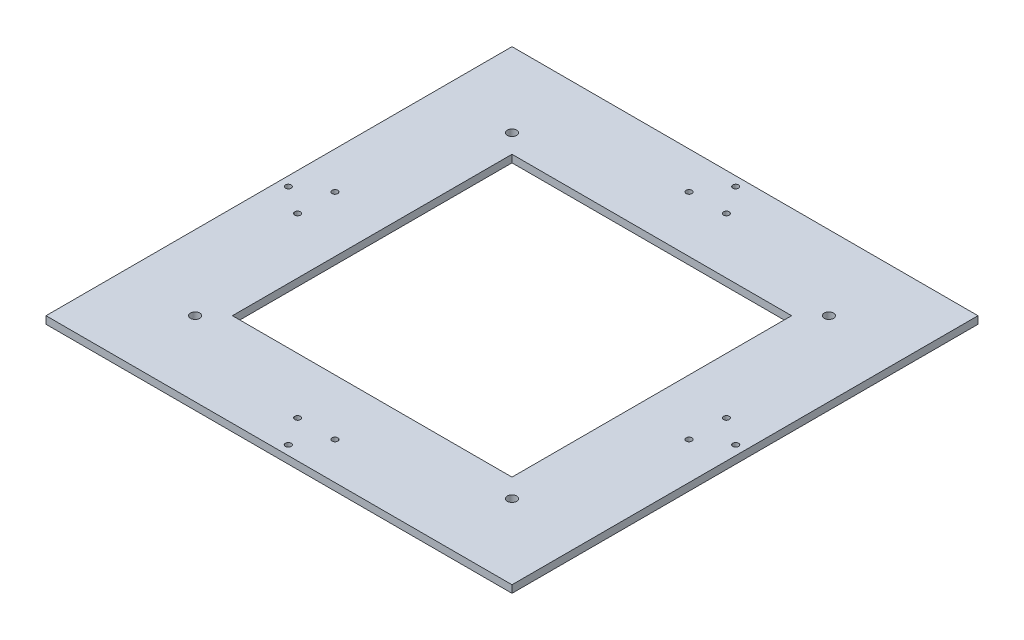
SolidWorks part; units mm, degrees
ref_plane "Alzado" through (0, 0, 0) normal (0, 0, 1) x (1, 0, 0)
ref_plane "Planta" through (0, 0, 0) normal (0, 1, 0) x (1, 0, 0)
ref_plane "Vista lateral" through (0, 0, 0) normal (1, 0, 0) x (0, 0, -1)
sketch "Croquis1" plane through (0, 0, 0) normal (0, 1, 0) x (1, 0, 0)
  line L0 (125, 40) -> (125, 0) construction
  line L1 (0, 0) -> (250, 0)
  line L2 (0, 0) -> (0, 250)
  line L3 (0, 250) -> (250, 250)
  line L4 (250, 0) -> (250, 250)
  line L5 (40, 40) -> (210, 40) construction
  line L6 (40, 40) -> (40, 210) construction
  line L7 (40, 210) -> (210, 210) construction
  line L8 (210, 40) -> (210, 210) construction
  line L9 (210, 125) -> (250, 125) construction
  circle A0 centre (40, 210) radius 2.5
  circle A1 centre (210, 210) radius 2.5
  circle A2 centre (210, 40) radius 2.5
  circle A3 centre (40, 40) radius 2.5
  dimension "D3" = 5
  dimension "D1" = 250
  dimension "D2" = 170
extrude "Saliente-Extruir1" add sketch "Croquis1" along normal blind 4
sketch "Croquis2" plane through (0, 4, 0) normal (0, 1, 0) x (1, 0, 0)
  line L0 (50, 125) -> (0, 125) construction
  line L1 (50, 50) -> (200, 50)
  line L2 (50, 50) -> (50, 150.0904)
  line L3 (50, 200) -> (200, 200)
  line L4 (200, 50) -> (200, 200)
  line L5 (0, 250) -> (0, 0) construction
  line L6 (125, 50) -> (125, 0) construction
  line L7 (0, 0) -> (250, 0) construction
  line L8 (50, 125) -> (200, 125) construction
  line L9 (125, 200) -> (125, 50) construction
  line L10 (48, 151.5) -> (48, 125) construction
  line L19 (50, 50) -> (200, 50) construction
  line L20 (50, 50) -> (50, 200) construction
  line L21 (50, 200) -> (200, 200) construction
  line L22 (200, 50) -> (200, 200) construction
  line L24 (50, 150.0904) -> (50, 172.9096)
  line L27 (59.9079, 125) -> (59.9079, 200) construction
  line L28 (50, 161.5) -> (34.9079, 161.5) construction
  line L29 (50, 150.0904) -> (125, 150.0904) construction
  line L30 (88.5, 200) -> (88.5, 125.0904) construction
  line L31 (78.5, 200) -> (98.5, 200)
  line L44 (121.5, 50) -> (101.5, 50)
  line L59 (88.5, 162.5452) -> (125, 162.5452) construction
  line L60 (42.454, 161.5) -> (42.454, 125) construction
  line L61 (25, 103.5) -> (25, 123.5) [skipped]
  line L65 (50, 150.0904) -> (50, 200)
  line L66 (125.0904, 175) -> (147.9096, 175) [skipped]
  line L69 (175, 146.5) -> (175, 126.5) [skipped]
  line L71 (150, 99.9096) -> (150, 77.0904) [skipped]
  line L72 (74.9096, 75) -> (52.0904, 75) [skipped]
  point P18 (50, 125)
  point P19 (125, 200)
  dimension "D1" = 150
  dimension "D2" = 150
  dimension "D4" = 4
  dimension "D6" = 36.5
extrude "Cortar-Extruir1" cut sketch "Croquis2" against normal blind 4
sketch "Croquis3" plane through (0, 4, 0) normal (0, 1, 0) x (1, 0, 0)
  line L0 (75, 175) -> (75, 75)
  line L1 (50, 200) -> (200, 200)
  line L2 (50, 200) -> (50, 50)
  line L3 (50, 50) -> (200, 50)
  line L4 (200, 200) -> (200, 50)
  line L5 (75, 75) -> (175, 75)
  line L6 (175, 175) -> (175, 75)
  line L7 (75, 175) -> (175, 175)
  dimension "D1" = 25
extrude "Saliente-Extruir2" add sketch "Croquis3" against normal up to surface (4 mm away) up to face at (125, 0, -125)
sketch "Croquis4" plane through (0, 4, 0) normal (0, 1, 0) x (1, 0, 0)
  line L0 (125, 0) -> (125, 75) construction
  line L1 (0, 0) -> (250, 0) construction
  line L2 (75, 75) -> (175, 75) construction
  line L3 (115, 20) -> (125, 20) construction
  line L4 (125, 20) -> (135, 20) construction
  circle A0 centre (115, 20) radius 1.55
  circle A1 centre (135, 20) radius 1.55
  circle A2 centre (125, 5) radius 1.55
  dimension "D1" = 3.1
  dimension "D4" = 5
  dimension "D2" = 10
  dimension "D3" = 20
extrude "Cortar-Extruir2" cut sketch "Croquis4" against normal blind 10
sketch "Croquis5" plane through (0, 4, 0) normal (0, 1, 0) x (1, 0, 0)
  line L0 (75, 175) -> (75, 75) construction
  line L1 (75, 75) -> (175, 75) construction
  line L2 (175, 75) -> (175, 175) construction
  line L3 (175, 175) -> (75, 175) construction
  line L4 (75, 175) -> (75, 75)
  line L5 (75, 75) -> (175, 75)
  line L6 (175, 75) -> (175, 175)
  line L7 (175, 175) -> (75, 175)
  line L8 (50, 200) -> (50, 50)
  line L9 (50, 50) -> (200, 50)
  line L10 (200, 50) -> (200, 200)
  line L11 (200, 200) -> (50, 200)
  dimension "D1" = 25
extrude "Cortar-Extruir3" cut sketch "Croquis5" against normal blind 10
sketch "Croquis6" plane through (0, 4, 0) normal (0, 1, 0) x (1, 0, 0)
  line L0 (50, 125) -> (200, 125) construction
  line L1 (50, 200) -> (50, 50) construction
  line L2 (200, 50) -> (200, 200) construction
  line L3 (125, 125) -> (125, 50) construction
  line L4 (50, 50) -> (200, 50) construction
  circle A0 centre (125, 5) radius 1.55 construction
  circle A1 centre (115, 20) radius 1.55 construction
  circle A2 centre (135, 20) radius 1.55 construction
  circle A3 centre (125, 5) radius 1.55
  circle A4 centre (115, 20) radius 1.55
  circle A5 centre (135, 20) radius 1.55
  circle A6 centre (20, 115) radius 1.55
  circle A7 centre (20, 135) radius 1.55
  circle A8 centre (5, 125) radius 1.55
  circle A9 centre (115, 230) radius 1.55
  circle A10 centre (135, 230) radius 1.55
  circle A11 centre (125, 245) radius 1.55
  circle A12 centre (230, 135) radius 1.55
  circle A13 centre (230, 115) radius 1.55
  circle A14 centre (245, 125) radius 1.55
  dimension "D1" = 4
extrude "Cortar-Extruir4" cut sketch "Croquis6" against normal blind 10
